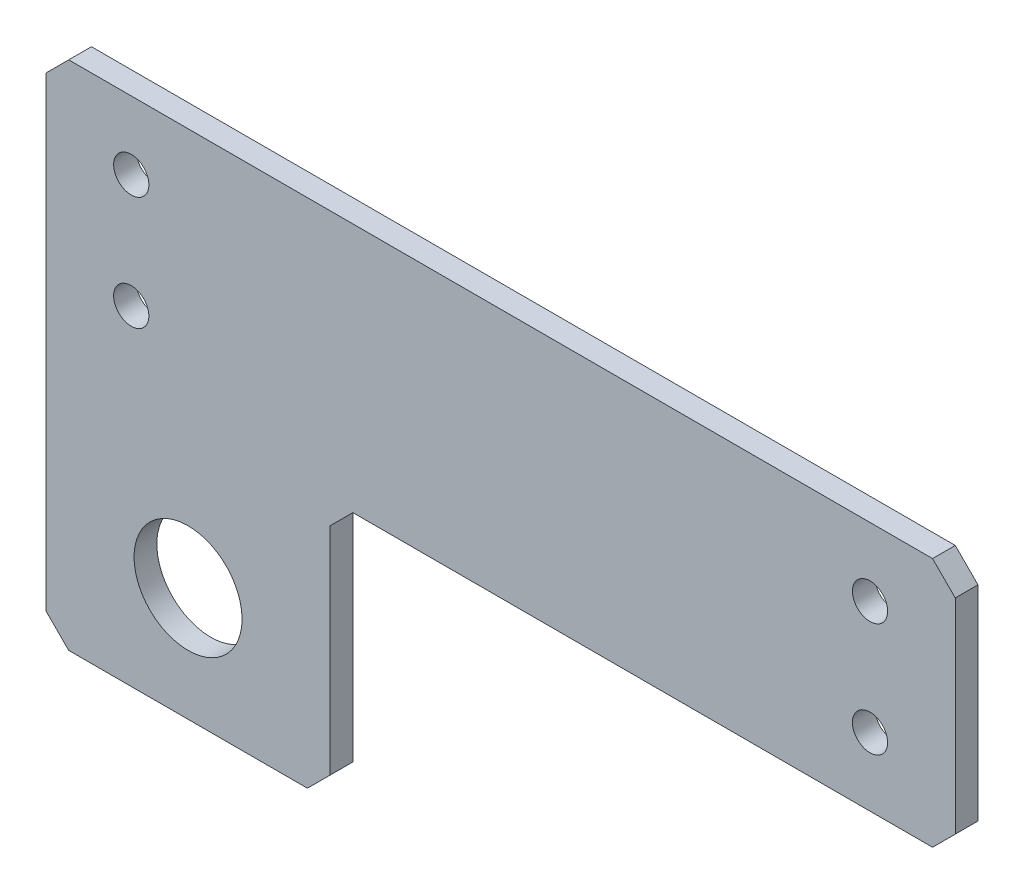
SolidWorks part; units mm, degrees
ref_plane "前基準面" through (0, 0, 0) normal (0, 0, 1) x (1, 0, 0)
ref_plane "上基準面" through (0, 0, 0) normal (0, 1, 0) x (1, 0, 0)
ref_plane "右基準面" through (0, 0, 0) normal (1, 0, 0) x (0, 0, -1)
sketch "草圖1" plane through (0, 0, 0) normal (0, 0, 1) x (1, 0, 0)
  line L1 (-80, -40) -> (80, -40)
  line L2 (-80, -40) -> (-80, 40)
  line L3 (-80, 40) -> (80, 40)
  line L4 (80, -40) -> (80, 40)
  line L5 (-80, -40) -> (80, 40) construction
  line L6 (-80, 40) -> (80, -40) construction
  point P0 (0, 0)
  dimension "D1" = 160
  dimension "D2" = 80
extrude "填料-伸長1" add sketch "草圖1" along normal blind 4
sketch "草圖2" plane through (0, 0, 4) normal (0, 0, 1) x (1, 0, 0)
  line L0 (80, 28) -> (65, 28) construction
  line L1 (80, -40) -> (80, 40) construction
  line L2 (65, 28) -> (65, 40) construction
  line L3 (80, 40) -> (-80, 40) construction
  circle A0 centre (65, 28) radius 3.1
  dimension "D3" = 6.2
  dimension "D1" = 12
  dimension "D2" = 15
extrude "除料-伸長1" cut sketch "草圖2" against normal through all
pattern_linear "直線複製排列1" count 2 spacing 20 along (0, -1, 0) count 2 spacing 130 along (-1, 0, 0) of "除料-伸長1"
sketch "草圖3" plane through (0, 0, 4) normal (0, 0, 1) x (1, 0, 0)
  line L0 (65, 28) -> (65, 8) construction
  line L2 (80, -4) -> (-30, -4)
  line L3 (80, -40) -> (80, 40) construction
  line L4 (-30, -4) -> (-30, -40)
  line L5 (-80, -40) -> (80, -40) construction
  line L6 (-80, 40) -> (-80, -40) construction
  line L7 (-30, -40) -> (80, -40)
  line L8 (80, -40) -> (80, -4)
  dimension "D1" = 36
  dimension "D2" = 50
extrude "除料-伸長2" cut sketch "草圖3" against normal through all
sketch "草圖4" plane through (0, -40, 0) normal (0, -1, 0) x (1, 0, 0)
  line L1 (-80, 0) -> (-30, 0)
  line L2 (-80, 0) -> (-80, 4)
  line L3 (-80, 4) -> (-30, 4)
  line L4 (-30, 0) -> (-30, 4)
extrude "填料-伸長2" add sketch "草圖4" along normal blind 10
chamfer "導角1" distance 4 angle 45 6 edges at (80, 40, 2) (-80, 40, 2) (-30, -4, 2) (80, -4, 2) (-80, -50, 2) (-30, -50, 2)
sketch "草圖5" plane through (0, 0, 4) normal (0, 0, 1) x (1, 0, 0)
  line L0 (-55, -50) -> (-55, -30) construction
  line L1 (-34, -50) -> (-76, -50) construction
  circle A0 centre (-55, -30) radius 9.5
  dimension "D1" = 19
  dimension "D2" = 20
extrude "除料-伸長3" cut sketch "草圖5" against normal through all
